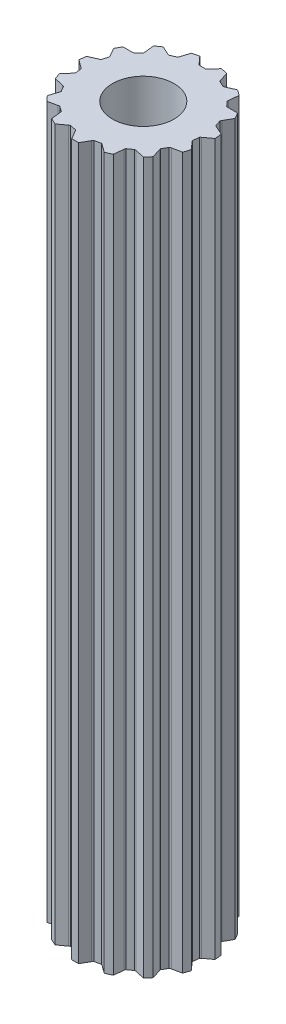
SolidWorks part; units mm, degrees
ref_plane "Front Plane" through (0, 0, 0) normal (0, 0, 1) x (1, 0, 0)
ref_plane "Top Plane" through (0, 0, 0) normal (0, 1, 0) x (1, 0, 0)
ref_plane "Right Plane" through (0, 0, 0) normal (1, 0, 0) x (0, 0, -1)
sketch "Sketch1" plane through (0, 0, 0) normal (0, 1, 0) x (1, 0, 0)
  line L0 (0, -15.875) -> (-1.7611, -12.8247)
  line L1 (0, -15.875) -> (1.7611, -12.8247)
  line L2 (0, 0) -> (0, -15.875) construction
  line L3 (0, -15.875) -> (-0.2097, -15.966) construction
  line L4 (-6.4569, -14.5025) -> (-3.6074, -12.4322)
  line L5 (-6.4569, -14.5025) -> (-6.8251, -10.9996)
  line L6 (-11.7974, -10.6224) -> (-8.3522, -9.8901)
  line L7 (-11.7974, -10.6224) -> (-10.709, -7.2726)
  line L8 (-15.098, -4.9056) -> (-11.6528, -5.6379)
  line L9 (-15.098, -4.9056) -> (-12.7412, -2.2881)
  line L10 (-15.788, 1.6594) -> (-12.9385, -0.4109)
  line L11 (-15.788, 1.6594) -> (-12.5704, 3.092)
  line L12 (-13.7482, 7.9375) -> (-11.9871, 4.8872)
  line L13 (-13.7482, 7.9375) -> (-10.226, 7.9375)
  line L14 (-9.3311, 12.8431) -> (-8.9629, 9.3403)
  line L15 (-9.3311, 12.8431) -> (-6.1134, 11.4105)
  line L16 (-3.3006, 15.5281) -> (-4.389, 12.1783)
  line L17 (-3.3006, 15.5281) -> (-0.9438, 12.9106)
  line L18 (3.3006, 15.5281) -> (0.9438, 12.9106)
  line L19 (3.3006, 15.5281) -> (4.389, 12.1783)
  line L20 (9.3311, 12.8431) -> (6.1134, 11.4105)
  line L21 (9.3311, 12.8431) -> (8.9629, 9.3403)
  line L22 (13.7482, 7.9375) -> (10.226, 7.9375)
  line L23 (13.7482, 7.9375) -> (11.9871, 4.8872)
  line L24 (15.788, 1.6594) -> (12.5704, 3.092)
  line L25 (15.788, 1.6594) -> (12.9385, -0.4109)
  line L26 (15.098, -4.9056) -> (12.7412, -2.2881)
  line L27 (15.098, -4.9056) -> (11.6528, -5.6379)
  line L28 (11.7974, -10.6224) -> (10.709, -7.2726)
  line L29 (11.7974, -10.6224) -> (8.3522, -9.8901)
  line L30 (6.4569, -14.5025) -> (6.8251, -10.9996)
  line L31 (6.4569, -14.5025) -> (3.6074, -12.4322)
  circle A0 centre (0, 0) radius 6.604
  circle A1 centre (0, 0) radius 15.875
  arc A2 (-11.8541, 4.5574) -> (-12.2689, 3.2807) centre (0, 0) ccw
  arc A3 (-11.8541, 4.5574) -> (-12.2689, 3.2807) centre (0, 0) ccw
  arc A4 (-11.8541, 4.5574) -> (-12.2689, 3.2807) centre (0, 0) ccw
  arc A5 (-11.8541, 4.5574) -> (-12.2689, 3.2807) centre (0, 0) ccw
  arc A6 (-11.8541, 4.5574) -> (-12.2689, 3.2807) centre (0, 0) ccw
  arc A7 (-11.8541, 4.5574) -> (-12.2689, 3.2807) centre (0, 0) ccw
  arc A8 (-11.8541, 4.5574) -> (-12.2689, 3.2807) centre (0, 0) ccw
  arc A9 (-11.8541, 4.5574) -> (-12.2689, 3.2807) centre (0, 0) ccw
  arc A10 (-11.8541, 4.5574) -> (-12.2689, 3.2807) centre (0, 0) ccw
  arc A11 (-11.8541, 4.5574) -> (-12.2689, 3.2807) centre (0, 0) ccw
  arc A12 (-11.8541, 4.5574) -> (-12.2689, 3.2807) centre (0, 0) ccw
  arc A13 (-11.8541, 4.5574) -> (-12.2689, 3.2807) centre (0, 0) ccw
  arc A14 (-11.8541, 4.5574) -> (-12.2689, 3.2807) centre (0, 0) ccw
  arc A15 (-11.8541, 4.5574) -> (-12.2689, 3.2807) centre (0, 0) ccw
  arc A16 (-11.8541, 4.5574) -> (-12.2689, 3.2807) centre (0, 0) ccw
  arc A17 (-8.9629, 9.3403) -> (-8.9756, 8.9849) centre (-10.226, 9.2075) cw
  arc A18 (-11.9871, 4.8872) -> (-11.8541, 4.5574) centre (-13.0869, 4.2522) cw
  arc A19 (-12.9385, -0.4109) -> (-12.6829, -0.6581) centre (-13.685, -1.4384) cw
  arc A20 (-11.6528, -5.6379) -> (-11.3188, -5.7598) centre (-11.9168, -6.8802) cw
  arc A21 (-8.3522, -9.8901) -> (-7.9975, -9.8656) centre (-8.0882, -11.1324) cw
  arc A22 (-3.6074, -12.4322) -> (-3.2933, -12.2656) centre (-2.8609, -13.4597) cw
  arc A23 (1.7611, -12.8247) -> (1.9803, -12.5447) centre (2.8609, -13.4597) cw
  arc A24 (6.8251, -10.9996) -> (6.9114, -10.6547) centre (8.0882, -11.1324) cw
  arc A25 (10.709, -7.2726) -> (10.6476, -6.9224) centre (11.9168, -6.8802) cw
  arc A26 (12.7412, -2.2881) -> (12.5426, -1.9932) centre (13.685, -1.4384) cw
  arc A27 (12.5704, 3.092) -> (12.2689, 3.2807) centre (13.0869, 4.2522) cw
  arc A28 (10.226, 7.9375) -> (9.8739, 7.9873) centre (10.226, 9.2075) cw
  arc A29 (6.1134, 11.4105) -> (5.7715, 11.3128) centre (5.5969, 12.5707) cw
  arc A30 (0.9438, 12.9106) -> (0.6712, 12.6823) centre (0, 13.7604) cw
  arc A31 (-4.389, 12.1783) -> (-4.5452, 11.8588) centre (-5.5969, 12.5707) cw
  circle A32 centre (0, 0) radius 14.605
  arc A33 (-12.5426, -1.9932) -> (-12.7412, -2.2881) centre (-13.685, -1.4384) cw
  arc A34 (-10.6476, -6.9224) -> (-10.709, -7.2726) centre (-11.9168, -6.8802) cw
  arc A35 (-6.9114, -10.6547) -> (-6.8251, -10.9996) centre (-8.0882, -11.1324) cw
  arc A36 (-1.9803, -12.5447) -> (-1.7611, -12.8247) centre (-2.8609, -13.4597) cw
  arc A37 (3.2933, -12.2656) -> (3.6074, -12.4322) centre (2.8609, -13.4597) cw
  arc A38 (7.9975, -9.8656) -> (8.3522, -9.8901) centre (8.0882, -11.1324) cw
  arc A39 (11.3188, -5.7598) -> (11.6528, -5.6379) centre (11.9168, -6.8802) cw
  arc A40 (12.6829, -0.6581) -> (12.9385, -0.4109) centre (13.685, -1.4384) cw
  arc A41 (11.8541, 4.5574) -> (11.9871, 4.8872) centre (13.0869, 4.2522) cw
  arc A42 (8.9756, 8.9849) -> (8.9629, 9.3403) centre (10.226, 9.2075) cw
  arc A43 (4.5452, 11.8588) -> (4.389, 12.1783) centre (5.5969, 12.5707) cw
  arc A44 (-0.6712, 12.6823) -> (-0.9438, 12.9106) centre (0, 13.7604) cw
  arc A45 (-5.7715, 11.3128) -> (-6.1134, 11.4105) centre (-5.5969, 12.5707) cw
  arc A46 (-9.8739, 7.9873) -> (-10.226, 7.9375) centre (-10.226, 9.2075) cw
  arc A47 (-12.2689, 3.2807) -> (-12.5704, 3.092) centre (-13.0869, 4.2522) cw
  arc A48 (-8.9756, 8.9849) -> (-9.8739, 7.9873) centre (0, 0) ccw
  arc A49 (-8.9756, 8.9849) -> (-9.8739, 7.9873) centre (0, 0) ccw
  arc A50 (-8.9756, 8.9849) -> (-9.8739, 7.9873) centre (0, 0) ccw
  arc A51 (-8.9756, 8.9849) -> (-9.8739, 7.9873) centre (0, 0) ccw
  arc A52 (-8.9756, 8.9849) -> (-9.8739, 7.9873) centre (0, 0) ccw
  arc A53 (-8.9756, 8.9849) -> (-9.8739, 7.9873) centre (0, 0) ccw
  arc A54 (-8.9756, 8.9849) -> (-9.8739, 7.9873) centre (0, 0) ccw
  arc A55 (-8.9756, 8.9849) -> (-9.8739, 7.9873) centre (0, 0) ccw
  arc A56 (-8.9756, 8.9849) -> (-9.8739, 7.9873) centre (0, 0) ccw
  arc A57 (-8.9756, 8.9849) -> (-9.8739, 7.9873) centre (0, 0) ccw
  arc A58 (-8.9756, 8.9849) -> (-9.8739, 7.9873) centre (0, 0) ccw
  arc A59 (-8.9756, 8.9849) -> (-9.8739, 7.9873) centre (0, 0) ccw
  arc A60 (-8.9756, 8.9849) -> (-9.8739, 7.9873) centre (0, 0) ccw
  arc A61 (-8.9756, 8.9849) -> (-9.8739, 7.9873) centre (0, 0) ccw
  arc A62 (-8.9756, 8.9849) -> (-9.8739, 7.9873) centre (0, 0) ccw
  arc A63 (-4.5452, 11.8588) -> (-5.7715, 11.3128) centre (0, 0) ccw
  arc A64 (-4.5452, 11.8588) -> (-5.7715, 11.3128) centre (0, 0) ccw
  arc A65 (-4.5452, 11.8588) -> (-5.7715, 11.3128) centre (0, 0) ccw
  arc A66 (-4.5452, 11.8588) -> (-5.7715, 11.3128) centre (0, 0) ccw
  arc A67 (-4.5452, 11.8588) -> (-5.7715, 11.3128) centre (0, 0) ccw
  arc A68 (-4.5452, 11.8588) -> (-5.7715, 11.3128) centre (0, 0) ccw
  arc A69 (-4.5452, 11.8588) -> (-5.7715, 11.3128) centre (0, 0) ccw
  arc A70 (-4.5452, 11.8588) -> (-5.7715, 11.3128) centre (0, 0) ccw
  arc A71 (-4.5452, 11.8588) -> (-5.7715, 11.3128) centre (0, 0) ccw
  arc A72 (-4.5452, 11.8588) -> (-5.7715, 11.3128) centre (0, 0) ccw
  arc A73 (-4.5452, 11.8588) -> (-5.7715, 11.3128) centre (0, 0) ccw
  arc A74 (-4.5452, 11.8588) -> (-5.7715, 11.3128) centre (0, 0) ccw
  arc A75 (-4.5452, 11.8588) -> (-5.7715, 11.3128) centre (0, 0) ccw
  arc A76 (-4.5452, 11.8588) -> (-5.7715, 11.3128) centre (0, 0) ccw
  arc A77 (-4.5452, 11.8588) -> (-5.7715, 11.3128) centre (0, 0) ccw
  arc A78 (0.6712, 12.6823) -> (-0.6712, 12.6823) centre (0, 0) ccw
  arc A79 (0.6712, 12.6823) -> (-0.6712, 12.6823) centre (0, 0) ccw
  arc A80 (0.6712, 12.6823) -> (-0.6712, 12.6823) centre (0, 0) ccw
  arc A81 (0.6712, 12.6823) -> (-0.6712, 12.6823) centre (0, 0) ccw
  arc A82 (0.6712, 12.6823) -> (-0.6712, 12.6823) centre (0, 0) ccw
  arc A83 (0.6712, 12.6823) -> (-0.6712, 12.6823) centre (0, 0) ccw
  arc A84 (0.6712, 12.6823) -> (-0.6712, 12.6823) centre (0, 0) ccw
  arc A85 (0.6712, 12.6823) -> (-0.6712, 12.6823) centre (0, 0) ccw
  arc A86 (0.6712, 12.6823) -> (-0.6712, 12.6823) centre (0, 0) ccw
  arc A87 (0.6712, 12.6823) -> (-0.6712, 12.6823) centre (0, 0) ccw
  arc A88 (0.6712, 12.6823) -> (-0.6712, 12.6823) centre (0, 0) ccw
  arc A89 (0.6712, 12.6823) -> (-0.6712, 12.6823) centre (0, 0) ccw
  arc A90 (0.6712, 12.6823) -> (-0.6712, 12.6823) centre (0, 0) ccw
  arc A91 (0.6712, 12.6823) -> (-0.6712, 12.6823) centre (0, 0) ccw
  arc A92 (0.6712, 12.6823) -> (-0.6712, 12.6823) centre (0, 0) ccw
  arc A93 (5.7715, 11.3128) -> (4.5452, 11.8588) centre (0, 0) ccw
  arc A94 (5.7715, 11.3128) -> (4.5452, 11.8588) centre (0, 0) ccw
  arc A95 (5.7715, 11.3128) -> (4.5452, 11.8588) centre (0, 0) ccw
  arc A96 (5.7715, 11.3128) -> (4.5452, 11.8588) centre (0, 0) ccw
  arc A97 (5.7715, 11.3128) -> (4.5452, 11.8588) centre (0, 0) ccw
  arc A98 (5.7715, 11.3128) -> (4.5452, 11.8588) centre (0, 0) ccw
  arc A99 (5.7715, 11.3128) -> (4.5452, 11.8588) centre (0, 0) ccw
  arc A100 (5.7715, 11.3128) -> (4.5452, 11.8588) centre (0, 0) ccw
  arc A101 (5.7715, 11.3128) -> (4.5452, 11.8588) centre (0, 0) ccw
  arc A102 (5.7715, 11.3128) -> (4.5452, 11.8588) centre (0, 0) ccw
  arc A103 (5.7715, 11.3128) -> (4.5452, 11.8588) centre (0, 0) ccw
  arc A104 (5.7715, 11.3128) -> (4.5452, 11.8588) centre (0, 0) ccw
  arc A105 (5.7715, 11.3128) -> (4.5452, 11.8588) centre (0, 0) ccw
  arc A106 (5.7715, 11.3128) -> (4.5452, 11.8588) centre (0, 0) ccw
  arc A107 (5.7715, 11.3128) -> (4.5452, 11.8588) centre (0, 0) ccw
  arc A108 (9.8739, 7.9873) -> (8.9756, 8.9849) centre (0, 0) ccw
  arc A109 (9.8739, 7.9873) -> (8.9756, 8.9849) centre (0, 0) ccw
  arc A110 (9.8739, 7.9873) -> (8.9756, 8.9849) centre (0, 0) ccw
  arc A111 (9.8739, 7.9873) -> (8.9756, 8.9849) centre (0, 0) ccw
  arc A112 (9.8739, 7.9873) -> (8.9756, 8.9849) centre (0, 0) ccw
  arc A113 (9.8739, 7.9873) -> (8.9756, 8.9849) centre (0, 0) ccw
  arc A114 (9.8739, 7.9873) -> (8.9756, 8.9849) centre (0, 0) ccw
  arc A115 (9.8739, 7.9873) -> (8.9756, 8.9849) centre (0, 0) ccw
  arc A116 (9.8739, 7.9873) -> (8.9756, 8.9849) centre (0, 0) ccw
  arc A117 (9.8739, 7.9873) -> (8.9756, 8.9849) centre (0, 0) ccw
  arc A118 (9.8739, 7.9873) -> (8.9756, 8.9849) centre (0, 0) ccw
  arc A119 (9.8739, 7.9873) -> (8.9756, 8.9849) centre (0, 0) ccw
  arc A120 (9.8739, 7.9873) -> (8.9756, 8.9849) centre (0, 0) ccw
  arc A121 (9.8739, 7.9873) -> (8.9756, 8.9849) centre (0, 0) ccw
  arc A122 (9.8739, 7.9873) -> (8.9756, 8.9849) centre (0, 0) ccw
  arc A123 (12.2689, 3.2807) -> (11.8541, 4.5574) centre (0, 0) ccw
  arc A124 (12.2689, 3.2807) -> (11.8541, 4.5574) centre (0, 0) ccw
  arc A125 (12.2689, 3.2807) -> (11.8541, 4.5574) centre (0, 0) ccw
  arc A126 (12.2689, 3.2807) -> (11.8541, 4.5574) centre (0, 0) ccw
  arc A127 (12.2689, 3.2807) -> (11.8541, 4.5574) centre (0, 0) ccw
  arc A128 (12.2689, 3.2807) -> (11.8541, 4.5574) centre (0, 0) ccw
  arc A129 (12.2689, 3.2807) -> (11.8541, 4.5574) centre (0, 0) ccw
  arc A130 (12.2689, 3.2807) -> (11.8541, 4.5574) centre (0, 0) ccw
  arc A131 (12.2689, 3.2807) -> (11.8541, 4.5574) centre (0, 0) ccw
  arc A132 (12.2689, 3.2807) -> (11.8541, 4.5574) centre (0, 0) ccw
  arc A133 (12.2689, 3.2807) -> (11.8541, 4.5574) centre (0, 0) ccw
  arc A134 (12.2689, 3.2807) -> (11.8541, 4.5574) centre (0, 0) ccw
  arc A135 (12.2689, 3.2807) -> (11.8541, 4.5574) centre (0, 0) ccw
  arc A136 (12.2689, 3.2807) -> (11.8541, 4.5574) centre (0, 0) ccw
  arc A137 (12.2689, 3.2807) -> (11.8541, 4.5574) centre (0, 0) ccw
  arc A138 (12.5426, -1.9932) -> (12.6829, -0.6581) centre (0, 0) ccw
  arc A139 (12.5426, -1.9932) -> (12.6829, -0.6581) centre (0, 0) ccw
  arc A140 (12.5426, -1.9932) -> (12.6829, -0.6581) centre (0, 0) ccw
  arc A141 (12.5426, -1.9932) -> (12.6829, -0.6581) centre (0, 0) ccw
  arc A142 (12.5426, -1.9932) -> (12.6829, -0.6581) centre (0, 0) ccw
  arc A143 (12.5426, -1.9932) -> (12.6829, -0.6581) centre (0, 0) ccw
  arc A144 (12.5426, -1.9932) -> (12.6829, -0.6581) centre (0, 0) ccw
  arc A145 (12.5426, -1.9932) -> (12.6829, -0.6581) centre (0, 0) ccw
  arc A146 (12.5426, -1.9932) -> (12.6829, -0.6581) centre (0, 0) ccw
  arc A147 (12.5426, -1.9932) -> (12.6829, -0.6581) centre (0, 0) ccw
  arc A148 (12.5426, -1.9932) -> (12.6829, -0.6581) centre (0, 0) ccw
  arc A149 (12.5426, -1.9932) -> (12.6829, -0.6581) centre (0, 0) ccw
  arc A150 (12.5426, -1.9932) -> (12.6829, -0.6581) centre (0, 0) ccw
  arc A151 (12.5426, -1.9932) -> (12.6829, -0.6581) centre (0, 0) ccw
  arc A152 (12.5426, -1.9932) -> (12.6829, -0.6581) centre (0, 0) ccw
  arc A153 (10.6476, -6.9224) -> (11.3188, -5.7598) centre (0, 0) ccw
  arc A154 (10.6476, -6.9224) -> (11.3188, -5.7598) centre (0, 0) ccw
  arc A155 (10.6476, -6.9224) -> (11.3188, -5.7598) centre (0, 0) ccw
  arc A156 (10.6476, -6.9224) -> (11.3188, -5.7598) centre (0, 0) ccw
  arc A157 (10.6476, -6.9224) -> (11.3188, -5.7598) centre (0, 0) ccw
  arc A158 (10.6476, -6.9224) -> (11.3188, -5.7598) centre (0, 0) ccw
  arc A159 (10.6476, -6.9224) -> (11.3188, -5.7598) centre (0, 0) ccw
  arc A160 (10.6476, -6.9224) -> (11.3188, -5.7598) centre (0, 0) ccw
  arc A161 (10.6476, -6.9224) -> (11.3188, -5.7598) centre (0, 0) ccw
  arc A162 (10.6476, -6.9224) -> (11.3188, -5.7598) centre (0, 0) ccw
  arc A163 (10.6476, -6.9224) -> (11.3188, -5.7598) centre (0, 0) ccw
  arc A164 (10.6476, -6.9224) -> (11.3188, -5.7598) centre (0, 0) ccw
  arc A165 (10.6476, -6.9224) -> (11.3188, -5.7598) centre (0, 0) ccw
  arc A166 (10.6476, -6.9224) -> (11.3188, -5.7598) centre (0, 0) ccw
  arc A167 (10.6476, -6.9224) -> (11.3188, -5.7598) centre (0, 0) ccw
  arc A168 (6.9114, -10.6547) -> (7.9975, -9.8656) centre (0, 0) ccw
  arc A169 (6.9114, -10.6547) -> (7.9975, -9.8656) centre (0, 0) ccw
  arc A170 (6.9114, -10.6547) -> (7.9975, -9.8656) centre (0, 0) ccw
  arc A171 (6.9114, -10.6547) -> (7.9975, -9.8656) centre (0, 0) ccw
  arc A172 (6.9114, -10.6547) -> (7.9975, -9.8656) centre (0, 0) ccw
  arc A173 (6.9114, -10.6547) -> (7.9975, -9.8656) centre (0, 0) ccw
  arc A174 (6.9114, -10.6547) -> (7.9975, -9.8656) centre (0, 0) ccw
  arc A175 (6.9114, -10.6547) -> (7.9975, -9.8656) centre (0, 0) ccw
  arc A176 (6.9114, -10.6547) -> (7.9975, -9.8656) centre (0, 0) ccw
  arc A177 (6.9114, -10.6547) -> (7.9975, -9.8656) centre (0, 0) ccw
  arc A178 (6.9114, -10.6547) -> (7.9975, -9.8656) centre (0, 0) ccw
  arc A179 (6.9114, -10.6547) -> (7.9975, -9.8656) centre (0, 0) ccw
  arc A180 (6.9114, -10.6547) -> (7.9975, -9.8656) centre (0, 0) ccw
  arc A181 (6.9114, -10.6547) -> (7.9975, -9.8656) centre (0, 0) ccw
  arc A182 (6.9114, -10.6547) -> (7.9975, -9.8656) centre (0, 0) ccw
  arc A183 (1.9803, -12.5447) -> (3.2933, -12.2656) centre (0, 0) ccw
  arc A184 (1.9803, -12.5447) -> (3.2933, -12.2656) centre (0, 0) ccw
  arc A185 (1.9803, -12.5447) -> (3.2933, -12.2656) centre (0, 0) ccw
  arc A186 (1.9803, -12.5447) -> (3.2933, -12.2656) centre (0, 0) ccw
  arc A187 (1.9803, -12.5447) -> (3.2933, -12.2656) centre (0, 0) ccw
  arc A188 (1.9803, -12.5447) -> (3.2933, -12.2656) centre (0, 0) ccw
  arc A189 (1.9803, -12.5447) -> (3.2933, -12.2656) centre (0, 0) ccw
  arc A190 (1.9803, -12.5447) -> (3.2933, -12.2656) centre (0, 0) ccw
  arc A191 (1.9803, -12.5447) -> (3.2933, -12.2656) centre (0, 0) ccw
  arc A192 (1.9803, -12.5447) -> (3.2933, -12.2656) centre (0, 0) ccw
  arc A193 (1.9803, -12.5447) -> (3.2933, -12.2656) centre (0, 0) ccw
  arc A194 (1.9803, -12.5447) -> (3.2933, -12.2656) centre (0, 0) ccw
  arc A195 (1.9803, -12.5447) -> (3.2933, -12.2656) centre (0, 0) ccw
  arc A196 (1.9803, -12.5447) -> (3.2933, -12.2656) centre (0, 0) ccw
  arc A197 (1.9803, -12.5447) -> (3.2933, -12.2656) centre (0, 0) ccw
  arc A198 (-3.2933, -12.2656) -> (-1.9803, -12.5447) centre (0, 0) ccw
  arc A199 (-3.2933, -12.2656) -> (-1.9803, -12.5447) centre (0, 0) ccw
  arc A200 (-3.2933, -12.2656) -> (-1.9803, -12.5447) centre (0, 0) ccw
  arc A201 (-3.2933, -12.2656) -> (-1.9803, -12.5447) centre (0, 0) ccw
  arc A202 (-3.2933, -12.2656) -> (-1.9803, -12.5447) centre (0, 0) ccw
  arc A203 (-3.2933, -12.2656) -> (-1.9803, -12.5447) centre (0, 0) ccw
  arc A204 (-3.2933, -12.2656) -> (-1.9803, -12.5447) centre (0, 0) ccw
  arc A205 (-3.2933, -12.2656) -> (-1.9803, -12.5447) centre (0, 0) ccw
  arc A206 (-3.2933, -12.2656) -> (-1.9803, -12.5447) centre (0, 0) ccw
  arc A207 (-3.2933, -12.2656) -> (-1.9803, -12.5447) centre (0, 0) ccw
  arc A208 (-3.2933, -12.2656) -> (-1.9803, -12.5447) centre (0, 0) ccw
  arc A209 (-3.2933, -12.2656) -> (-1.9803, -12.5447) centre (0, 0) ccw
  arc A210 (-3.2933, -12.2656) -> (-1.9803, -12.5447) centre (0, 0) ccw
  arc A211 (-3.2933, -12.2656) -> (-1.9803, -12.5447) centre (0, 0) ccw
  arc A212 (-3.2933, -12.2656) -> (-1.9803, -12.5447) centre (0, 0) ccw
  arc A213 (-7.9975, -9.8656) -> (-6.9114, -10.6547) centre (0, 0) ccw
  arc A214 (-7.9975, -9.8656) -> (-6.9114, -10.6547) centre (0, 0) ccw
  arc A215 (-7.9975, -9.8656) -> (-6.9114, -10.6547) centre (0, 0) ccw
  arc A216 (-7.9975, -9.8656) -> (-6.9114, -10.6547) centre (0, 0) ccw
  arc A217 (-7.9975, -9.8656) -> (-6.9114, -10.6547) centre (0, 0) ccw
  arc A218 (-7.9975, -9.8656) -> (-6.9114, -10.6547) centre (0, 0) ccw
  arc A219 (-7.9975, -9.8656) -> (-6.9114, -10.6547) centre (0, 0) ccw
  arc A220 (-7.9975, -9.8656) -> (-6.9114, -10.6547) centre (0, 0) ccw
  arc A221 (-7.9975, -9.8656) -> (-6.9114, -10.6547) centre (0, 0) ccw
  arc A222 (-7.9975, -9.8656) -> (-6.9114, -10.6547) centre (0, 0) ccw
  arc A223 (-7.9975, -9.8656) -> (-6.9114, -10.6547) centre (0, 0) ccw
  arc A224 (-7.9975, -9.8656) -> (-6.9114, -10.6547) centre (0, 0) ccw
  arc A225 (-7.9975, -9.8656) -> (-6.9114, -10.6547) centre (0, 0) ccw
  arc A226 (-7.9975, -9.8656) -> (-6.9114, -10.6547) centre (0, 0) ccw
  arc A227 (-7.9975, -9.8656) -> (-6.9114, -10.6547) centre (0, 0) ccw
  arc A228 (-11.3188, -5.7598) -> (-10.6476, -6.9224) centre (0, 0) ccw
  arc A229 (-11.3188, -5.7598) -> (-10.6476, -6.9224) centre (0, 0) ccw
  arc A230 (-11.3188, -5.7598) -> (-10.6476, -6.9224) centre (0, 0) ccw
  arc A231 (-11.3188, -5.7598) -> (-10.6476, -6.9224) centre (0, 0) ccw
  arc A232 (-11.3188, -5.7598) -> (-10.6476, -6.9224) centre (0, 0) ccw
  arc A233 (-11.3188, -5.7598) -> (-10.6476, -6.9224) centre (0, 0) ccw
  arc A234 (-11.3188, -5.7598) -> (-10.6476, -6.9224) centre (0, 0) ccw
  arc A235 (-11.3188, -5.7598) -> (-10.6476, -6.9224) centre (0, 0) ccw
  arc A236 (-11.3188, -5.7598) -> (-10.6476, -6.9224) centre (0, 0) ccw
  arc A237 (-11.3188, -5.7598) -> (-10.6476, -6.9224) centre (0, 0) ccw
  arc A238 (-11.3188, -5.7598) -> (-10.6476, -6.9224) centre (0, 0) ccw
  arc A239 (-11.3188, -5.7598) -> (-10.6476, -6.9224) centre (0, 0) ccw
  arc A240 (-11.3188, -5.7598) -> (-10.6476, -6.9224) centre (0, 0) ccw
  arc A241 (-11.3188, -5.7598) -> (-10.6476, -6.9224) centre (0, 0) ccw
  arc A242 (-11.3188, -5.7598) -> (-10.6476, -6.9224) centre (0, 0) ccw
  arc A243 (-12.6829, -0.6581) -> (-12.5426, -1.9932) centre (0, 0) ccw
  arc A244 (-12.6829, -0.6581) -> (-12.5426, -1.9932) centre (0, 0) ccw
  arc A245 (-12.6829, -0.6581) -> (-12.5426, -1.9932) centre (0, 0) ccw
  arc A246 (-12.6829, -0.6581) -> (-12.5426, -1.9932) centre (0, 0) ccw
  arc A247 (-12.6829, -0.6581) -> (-12.5426, -1.9932) centre (0, 0) ccw
  arc A248 (-12.6829, -0.6581) -> (-12.5426, -1.9932) centre (0, 0) ccw
  arc A249 (-12.6829, -0.6581) -> (-12.5426, -1.9932) centre (0, 0) ccw
  arc A250 (-12.6829, -0.6581) -> (-12.5426, -1.9932) centre (0, 0) ccw
  arc A251 (-12.6829, -0.6581) -> (-12.5426, -1.9932) centre (0, 0) ccw
  arc A252 (-12.6829, -0.6581) -> (-12.5426, -1.9932) centre (0, 0) ccw
  arc A253 (-12.6829, -0.6581) -> (-12.5426, -1.9932) centre (0, 0) ccw
  arc A254 (-12.6829, -0.6581) -> (-12.5426, -1.9932) centre (0, 0) ccw
  arc A255 (-12.6829, -0.6581) -> (-12.5426, -1.9932) centre (0, 0) ccw
  arc A256 (-12.6829, -0.6581) -> (-12.5426, -1.9932) centre (0, 0) ccw
  arc A257 (-12.6829, -0.6581) -> (-12.5426, -1.9932) centre (0, 0) ccw
  point P68 (0, 0)
  dimension "D1" = 13.208
  dimension "D2" = 31.75
  dimension "D3" = 25.4
  dimension "D7" = 1.27
  dimension "D8" = 29.21
  dimension "D4" = 30
  dimension "D5" = 30
  dimension "D6" = 15
extrude "Boss-Extrude3" add sketch "Sketch1" along normal blind 152.4 contours A19 A243 A33 L9 A32 L8 A20 A228 A34 L7 L6 A21 A213 A35 L5 L4 A22 A198 A36 L0 L1 A23 A183 A37 L31 L30 A24 A168 A38 L29 L28 A25 A153 A39 L27 L26 A26 A138 A40 L25 L24 A27 A123 A41
